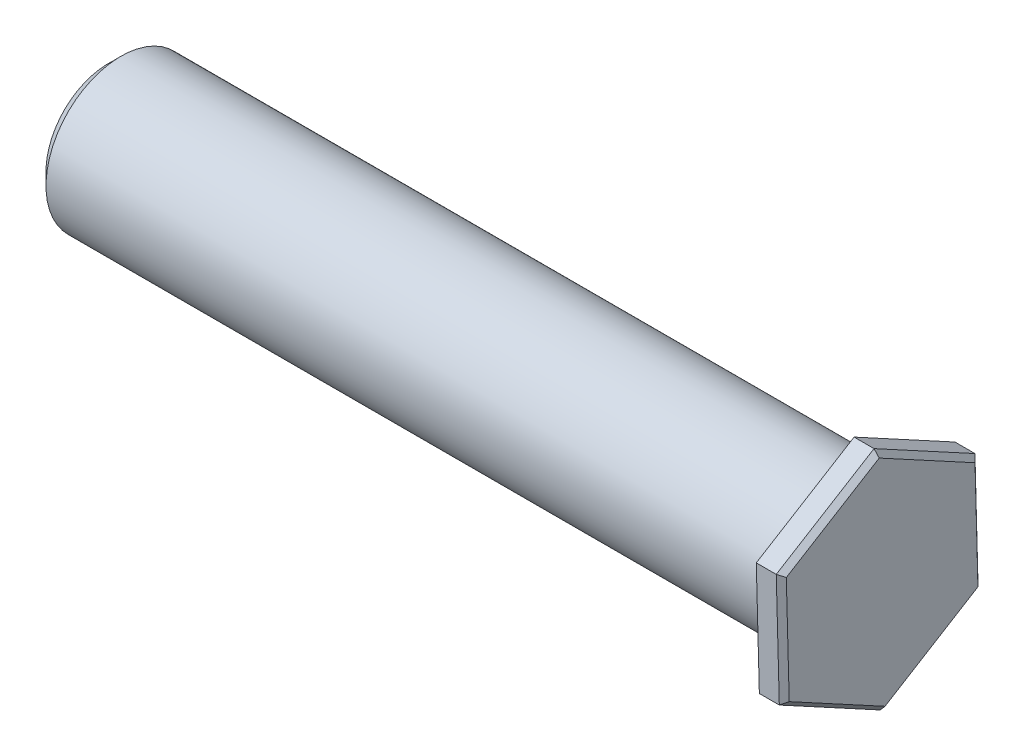
SolidWorks part; units mm, degrees
ref_plane "Front Plane" through (0, 0, 0) normal (0, 0, 1) x (1, 0, 0)
ref_plane "Top Plane" through (0, 0, 0) normal (0, 1, 0) x (1, 0, 0)
ref_plane "Right Plane" through (0, 0, 0) normal (1, 0, 0) x (0, 0, -1)
sketch "Sketch1" plane through (0, 0, 0) normal (1, 0, 0) x (0, 0, -1)
  circle A0 centre (0, 0) radius 15
  dimension "D1" = 30
extrude "Boss-Extrude1" add sketch "Sketch1" along normal blind 150
cosmetic thread "Cosmetic Thread1" parameters "D1"=5, "D2"=6.619
cosmetic thread "Cosmetic Thread2" parameters "D1"=60, "D2"=6.619
sketch "Sketch2" plane through (150, 0, 0) normal (1, 0, 0) x (0, 0, -1)
  line L1 (-20.2085, 10.9587) -> (-19.5948, -12.0218)
  line L2 (-19.5948, -12.0218) -> (0.6138, -22.9804)
  line L3 (0.6138, -22.9804) -> (20.2085, -10.9587)
  line L4 (20.2085, -10.9587) -> (19.5948, 12.0218)
  line L5 (19.5948, 12.0218) -> (-0.6138, 22.9804)
  line L6 (-0.6138, 22.9804) -> (-20.2085, 10.9587)
  circle A0 centre (0, 0) radius 19.9087 construction
extrude "Boss-Extrude2" add sketch "Sketch2" along normal blind 5
chamfer "Chamfer1" distance 1 angle 45 6 edges at (155, 17.5011, -9.4905) (155, 0.5315, -19.9017) (155, -16.9696, -10.4112) (155, -17.5011, 9.4905) (155, -0.5315, 19.9017) (155, 16.9696, 10.4112)
chamfer "Chamfer3" distance 2.5 angle 45 1 edges at (0, 0, -15)
